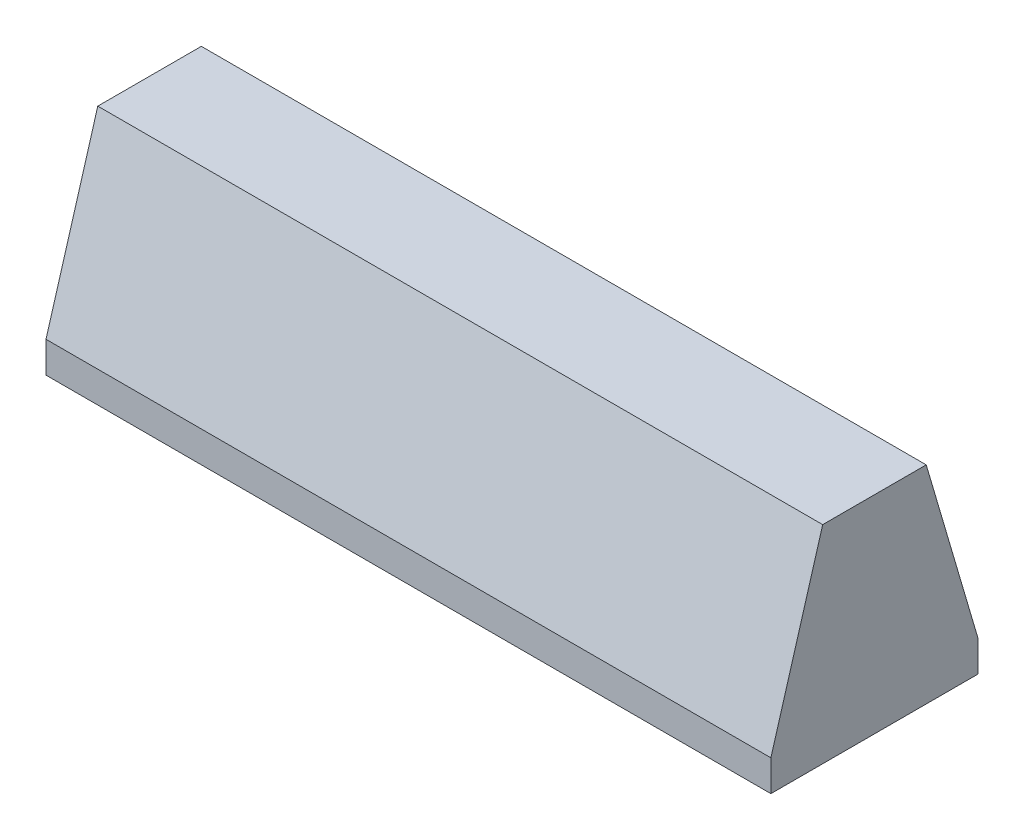
SolidWorks part; units mm, degrees
ref_plane "Front Plane" through (0, 0, 0) normal (0, 0, 1) x (1, 0, 0)
ref_plane "Top Plane" through (0, 0, 0) normal (0, 1, 0) x (1, 0, 0)
ref_plane "Right Plane" through (0, 0, 0) normal (1, 0, 0) x (0, 0, -1)
sketch "Sketch1" plane through (0, 0, 0) normal (0, 1, 0) x (1, 0, 0)
  line L1 (0, 0) -> (70, 0)
  line L2 (0, 0) -> (0, 20)
  line L3 (0, 20) -> (70, 20)
  line L4 (70, 0) -> (70, 20)
  dimension "D1" = 20
  dimension "D2" = 70
extrude "Boss-Extrude1" add sketch "Sketch1" along normal blind 20
chamfer "Chamfer1" distance 17 distance2 5 2 edges at (35, 20, -20) (35, 20, 0)
